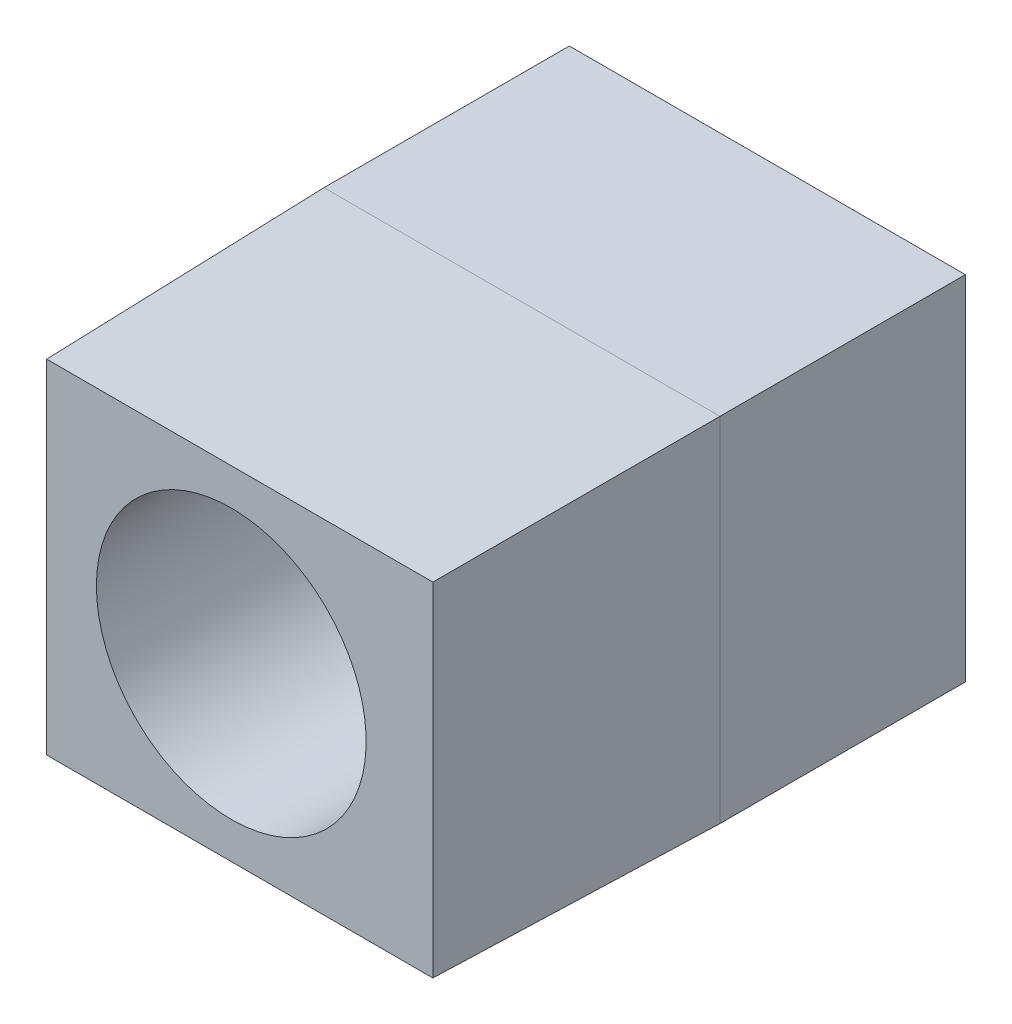
SolidWorks part; units mm, degrees
ref_plane "Front Plane" through (0, 0, 0) normal (0, 0, 1) x (1, 0, 0)
ref_plane "Top Plane" through (0, 0, 0) normal (0, 1, 0) x (1, 0, 0)
ref_plane "Right Plane" through (0, 0, 0) normal (1, 0, 0) x (0, 0, -1)
sketch "Sketch1" plane through (0, 0, 0) normal (0, 0, 1) x (1, 0, 0)
  line L1 (-291.0487, -259.2268) -> (291.0487, -259.2268)
  line L2 (-291.0487, -259.2268) -> (-291.0487, 259.2268)
  line L3 (-291.0487, 259.2268) -> (291.0487, 259.2268)
  line L4 (291.0487, -259.2268) -> (291.0487, 259.2268)
  line L5 (-291.0487, -259.2268) -> (291.0487, 259.2268) construction
  line L6 (-291.0487, 259.2268) -> (291.0487, -259.2268) construction
  point P0 (0, 0)
  point P6 (0, 0)
  point P7 (-142.2081, 17.0121)
  point P8 (322.4774, -54.532)
  point P9 (0, 0)
  point P10 (291.0487, 259.2268)
extrude "Boss-Extrude1" add sketch "Sketch1" along normal blind 414.782 draft 1 and the other way blind 360.68
sketch "Sketch2" plane through (0, 0, -360.68) normal (0, 0, -1) x (-1, 0, 0)
  circle A0 centre (12.4562, 0) radius 198.2402
extrude "Cut-Extrude1" cut sketch "Sketch2" against normal through all
